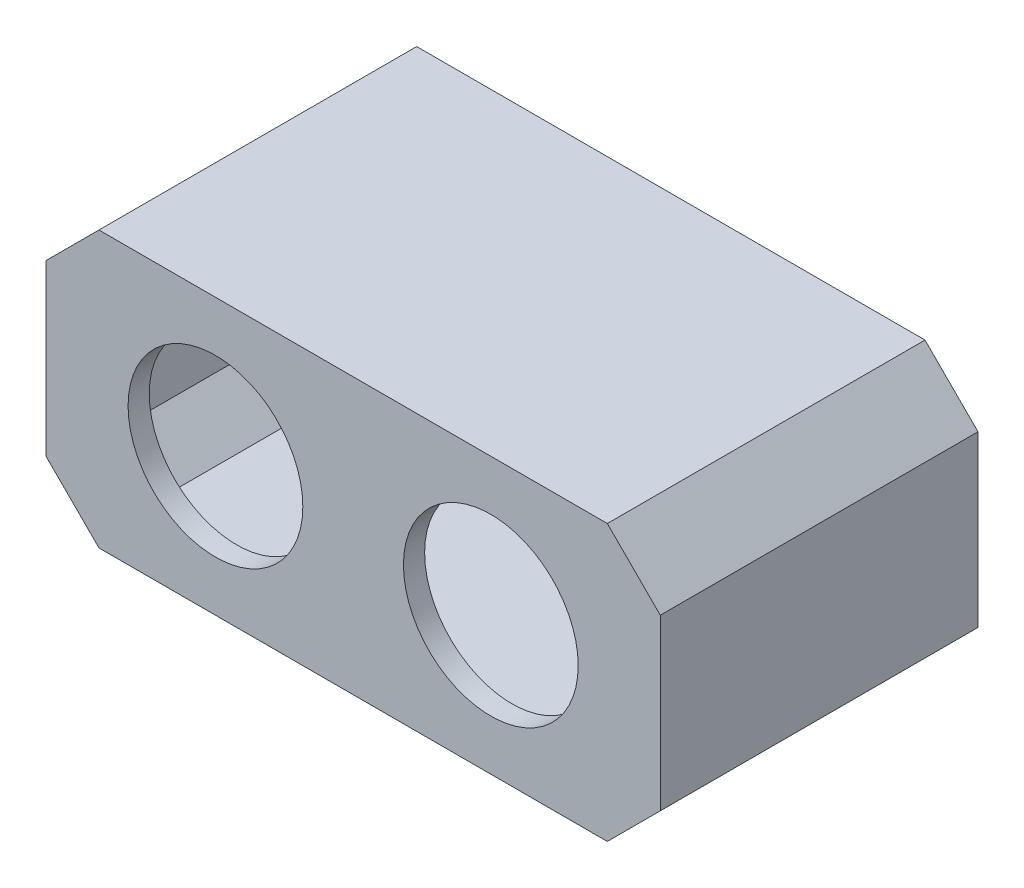
SolidWorks part; units mm, degrees
ref_plane "Front Plane" through (0, 0, 0) normal (0, 0, 1) x (1, 0, 0)
ref_plane "Top Plane" through (0, 0, 0) normal (0, 1, 0) x (1, 0, 0)
ref_plane "Right Plane" through (0, 0, 0) normal (1, 0, 0) x (0, 0, -1)
sketch "Sketch1" plane through (0, 0, 0) normal (0, 0, 1) x (1, 0, 0)
  line L1 (-29, -13) -> (29, -13)
  line L2 (-29, -13) -> (-29, 13)
  line L3 (-29, 13) -> (29, 13)
  line L4 (29, -13) -> (29, 13)
  line L5 (-29, -13) -> (29, 13) construction
  line L6 (-29, 13) -> (29, -13) construction
  point P0 (0, 0)
  dimension "D1" = 58
  dimension "D2" = 26
extrude "skull block" add sketch "Sketch1" against normal blind 30
chamfer "skull chamfer" distance 5 angle 45 4 edges at (29, -13, -15) (-29, -13, -15) (-29, 13, -15) (29, 13, -15)
shell "hollow skull" thickness 2
sketch "Sketch2" plane through (0, 0, 0) normal (0, 0, 1) x (1, 0, 0)
  line L0 (0, 0) -> (0, 50000) construction
  line L1 (0, 0) -> (50000, 0) construction
  circle A0 centre (13, 0) radius 8.25
  dimension "D1" = 16.5
  dimension "D2" = 13
extrude "eye hole" cut sketch "Sketch2" against normal up to next
mirror "mirror eye hole" about plane through (0, 0, 0) normal (1, 0, 0) of "eye hole"
sketch "Sketch3" plane through (0, -13, 0) normal (0, -1, 0) x (1, 0, 0)
  line L0 (0, 0) -> (0, -30) construction
  line L1 (-24, -30) -> (24, -30) construction
  circle A0 centre (0, -15) radius 12
  dimension "D1" = 24
extrude "neck mount" cut sketch "Sketch3" against normal blind 1
